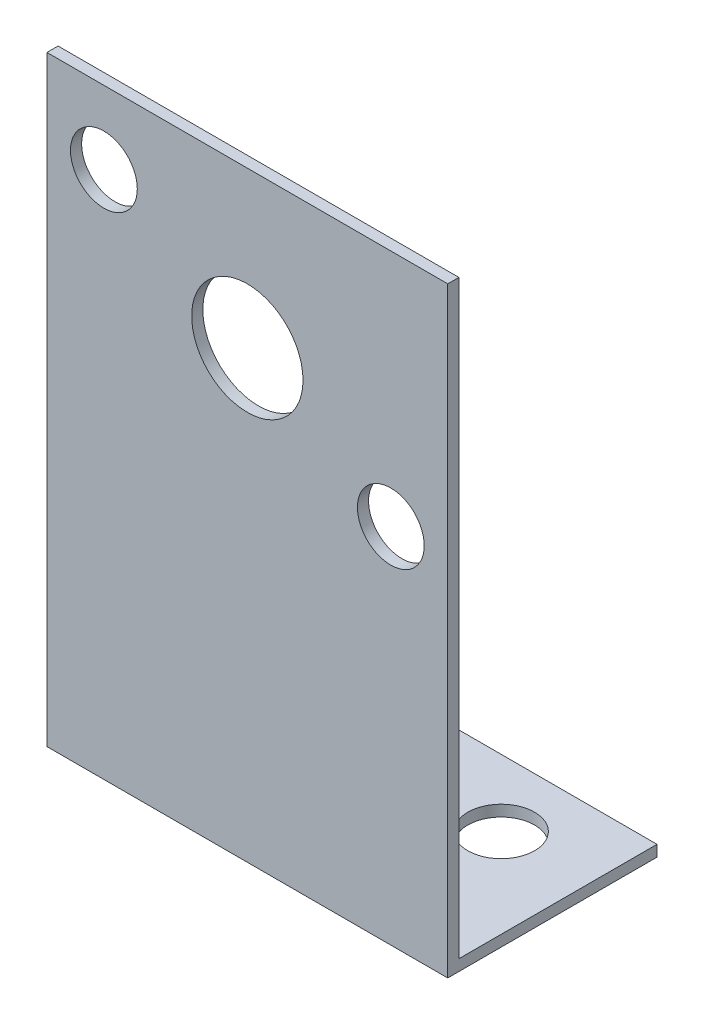
SolidWorks part; units mm, degrees
ref_plane "Front" through (0, 0, 0) normal (0, 0, 1) x (1, 0, 0)
ref_plane "Top" through (0, 0, 0) normal (0, 1, 0) x (1, 0, 0)
ref_plane "Right" through (0, 0, 0) normal (1, 0, 0) x (0, 0, -1)
sketch "Sketch1" plane through (0, 0, 0) normal (0, 0, 1) x (1, 0, 0)
  line L1 (-9, 7) -> (9, 7)
  line L2 (-9, 7) -> (-9, -20)
  line L3 (-9, -20) -> (9, -20)
  line L4 (9, 7) -> (9, -20)
  circle A0 centre (0, 0) radius 2.5
  dimension "D5" = 5
  dimension "D1" = 9
  dimension "D2" = 9
  dimension "D3" = 7
  dimension "D4" = 20
extrude "Extrude1" add sketch "Sketch1" along normal blind 0.5
sketch "Sketch2" plane through (0, 0, 0) normal (0, 0, -1) x (-1, 0, 0)
  line L0 (-9, -20) -> (-9, 7) construction
  line L1 (9, -20) -> (-9, -20)
  line L2 (9, -20) -> (9, -19.5)
  line L3 (9, -19.5) -> (-9, -19.5)
  line L4 (-9, -20) -> (-9, -19.5)
  dimension "D1" = 0.5
extrude "Extrude2" add sketch "Sketch2" along normal blind 8.9
sketch "Sketch3" plane through (0, -19.5, 0) normal (0, 1, 0) x (1, 0, 0)
  line L0 (-9, 8.9) -> (9, 8.9) construction
  line L1 (-9, 8.9) -> (-9, 0) construction
  line L2 (9, 8.9) -> (9, 0) construction
  circle A0 centre (-5, 5.9) radius 1.5
  circle A1 centre (5, 5.9) radius 1.5
  dimension "D4" = 3
  dimension "D5" = 3
  dimension "D1" = 3
  dimension "D2" = 4
  dimension "D3" = 4
extrude "Extrude3" cut sketch "Sketch3" against normal up to surface (0.5 mm away) up to face at (0, -20, -4.2)
sketch "Sketch4" plane through (0, 0, 0) normal (0, 0, -1) x (-1, 0, 0)
  circle A0 centre (-6.4432, -3.72) radius 1.5
  circle A1 centre (6.4432, 3.72) radius 1.5
  dimension "D1" = 3
  dimension "D2" = 3
  dimension "D3" = 7.44
  dimension "D4" = 7.44
  dimension "D5" = 3.72
  dimension "D6" = 3.72
extrude "Extrude4" cut sketch "Sketch4" against normal up to surface (0.5 mm away) up to face at (0, -6.5, 0.5)
